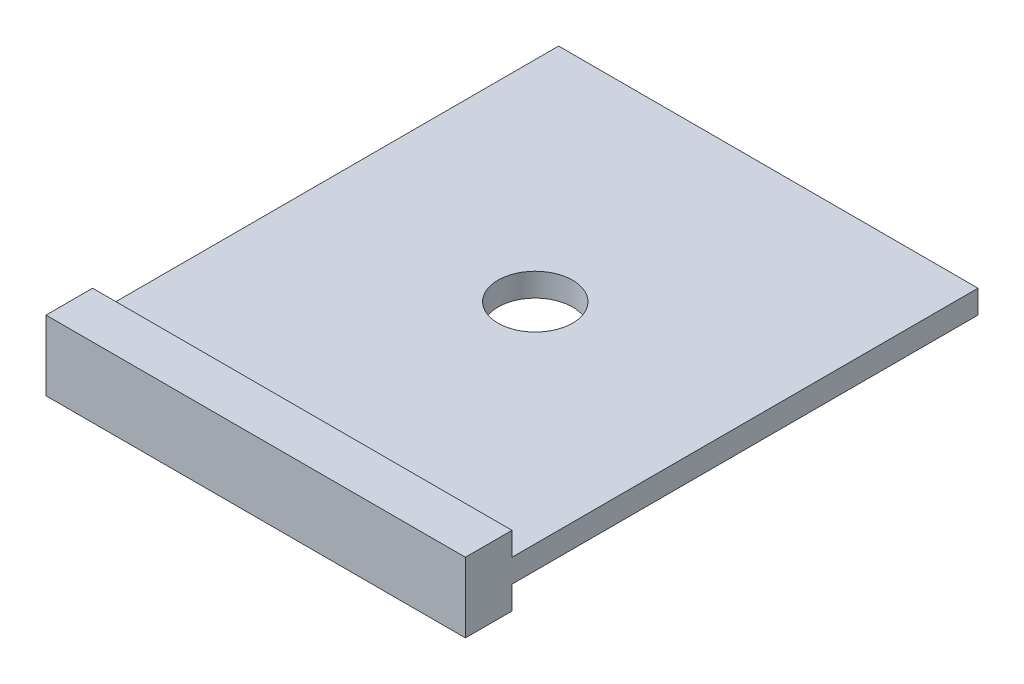
SolidWorks part; units mm, degrees
material "AISI 304"
ref_plane "Front Plane" through (0, 0, 0) normal (0, 0, 1) x (1, 0, 0)
ref_plane "Top Plane" through (0, 0, 0) normal (0, 1, 0) x (1, 0, 0)
ref_plane "Right Plane" through (0, 0, 0) normal (1, 0, 0) x (0, 0, -1)
sketch "Sketch1" plane through (0, 0, 0) normal (0, 1, 0) x (1, 0, 0)
  line L1 (0, 0) -> (18, 0)
  line L2 (0, 0) -> (0, 20)
  line L3 (0, 20) -> (18, 20)
  line L4 (18, 0) -> (18, 20)
  dimension "D1" = 18
  dimension "D2" = 20
extrude "Boss-Extrude1" add sketch "Sketch1" along normal blind 1 contours L2 L3 L4 L1
sketch "Sketch2" plane through (0, 0, 0) normal (0, 0, 1) x (1, 0, 0)
  line L0 (18, 1) -> (18, 0) construction
  line L1 (0, 2) -> (18, 2)
  line L2 (0, 2) -> (0, -1)
  line L3 (0, -1) -> (18, -1)
  line L4 (18, 2) -> (18, -1)
  line L5 (0, 1) -> (0, 0) construction
  line L6 (0, 1) -> (18, 1) construction
  line L7 (0, 0) -> (18, 0) construction
  dimension "D1" = 1
  dimension "D2" = 1
extrude "Boss-Extrude2" add sketch "Sketch2" along normal blind 2
sketch "Sketch3" plane through (0, 1, 0) normal (0, 1, 0) x (1, 0, 0)
  line L0 (0, 20) -> (18, 0) construction
  line L2 (18, 20) -> (0, 0) construction
  circle A0 centre (9, 10) radius 1.6
  dimension "D1" = 3.2
extrude "Cut-Extrude1" cut sketch "Sketch3" against normal through all
